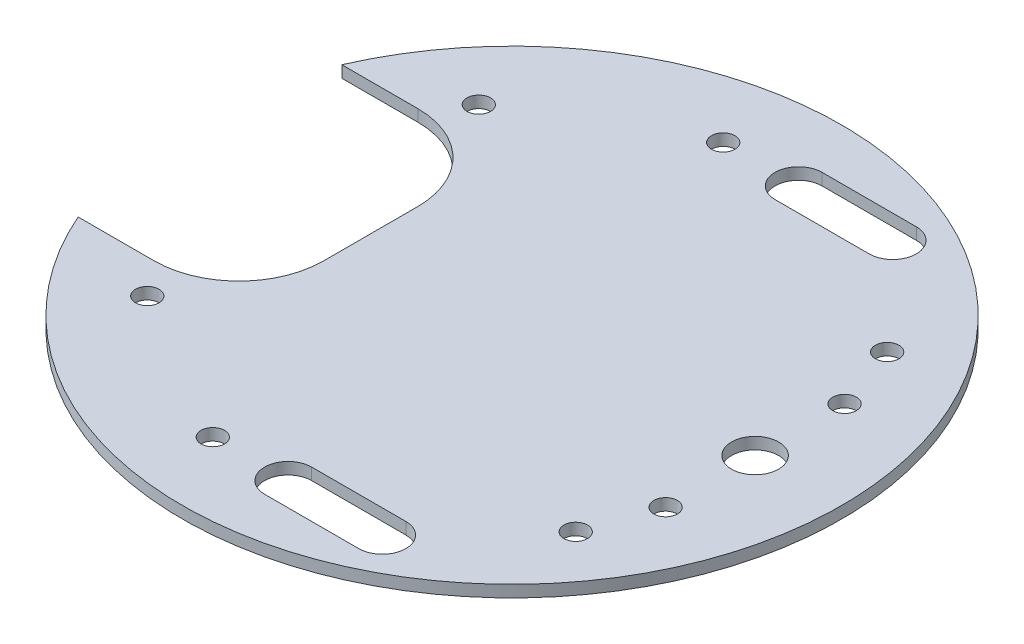
SolidWorks part; units mm, degrees
ref_plane "Front Plane" through (0, 0, 0) normal (0, 0, 1) x (1, 0, 0)
ref_plane "Top Plane" through (0, 0, 0) normal (0, 1, 0) x (1, 0, 0)
ref_plane "Right Plane" through (0, 0, 0) normal (1, 0, 0) x (0, 0, -1)
sketch "Sketch1" plane through (0, 0, 0) normal (0, 1, 0) x (1, 0, 0)
  line L0 (0, 0) -> (109.2336, 0) construction
  line L1 (0, 0) -> (-110.6657, 0) construction
  line L2 (27.076, -24.13) -> (65.5497, -24.13)
  line L3 (27.076, -24.13) -> (27.076, 24.13)
  line L4 (27.076, 24.13) -> (65.5497, 24.13)
  line L5 (65.5497, -24.13) -> (65.5497, 24.13)
  line L6 (27.076, -24.13) -> (65.5497, 24.13) construction
  line L7 (27.076, 24.13) -> (65.5497, -24.13) construction
  line L9 (-88.9, 35.56) -> (-38.1, 35.56)
  line L10 (-88.9, 35.56) -> (-88.9, -35.56)
  line L11 (-88.9, -35.56) -> (-38.1, -35.56)
  line L12 (-38.1, 35.56) -> (-38.1, -35.56)
  line L13 (-88.9, 35.56) -> (-38.1, -35.56) construction
  line L14 (-88.9, -35.56) -> (-38.1, 35.56) construction
  circle A0 centre (0, 0) radius 88.9
  circle A1 centre (0, 0) radius 69.85
  circle A2 centre (65.5497, 24.13) radius 3.175
  circle A3 centre (65.5497, -24.13) radius 3.175
  circle A4 centre (-53.6721, -44.7027) radius 3.175
  circle A5 centre (-11.8777, -68.8327) radius 3.175
  circle A6 centre (-11.8777, 68.8327) radius 3.175
  circle A7 centre (-53.6721, 44.7027) radius 3.175
  point P4 (46.3129, 0)
  point P12 (-63.5, 0)
  point P23 (0, 0)
  dimension "D1" = 177.8
  dimension "D2" = 139.7
  dimension "D4" = 3
  dimension "D3" = 48.26
  dimension "D5" = 71.12
  dimension "D6" = 50.8
  dimension "D7" = 63.5
sketch "Sketch2" plane through (0, 0, 0) normal (0, 1, 0) x (1, 0, 0)
  circle A0 centre (0, 0) radius 88.9
extrude "Boss-Extrude1" add sketch "Sketch2" along normal blind 3.175
sketch "Sketch3" plane through (0, 3.175, 0) normal (0, 1, 0) x (1, 0, 0)
  line L4 (27.076, -24.13) -> (65.5497, -24.13)
  line L5 (65.5497, -24.13) -> (65.5497, 24.13)
  line L6 (65.5497, 24.13) -> (27.076, 24.13)
  line L7 (27.076, 24.13) -> (27.076, -24.13)
  line L8 (27.076, -24.13) -> (65.5497, -24.13)
  line L9 (65.5497, -24.13) -> (65.5497, 24.13)
  line L10 (65.5497, 24.13) -> (27.076, 24.13)
  line L11 (27.076, 24.13) -> (27.076, -24.13)
  line L12 (-38.1, 35.56) -> (-88.9, 35.56)
  line L13 (-38.1, -35.56) -> (-38.1, 35.56)
  line L14 (-88.9, -35.56) -> (-38.1, -35.56)
  line L15 (-88.9, 35.56) -> (-88.9, -35.56)
  line L16 (-38.1, 35.56) -> (-88.9, 35.56)
  line L17 (-38.1, -35.56) -> (-38.1, 35.56)
  line L18 (-88.9, -35.56) -> (-38.1, -35.56)
  line L19 (-88.9, 35.56) -> (-88.9, -35.56)
  circle A1 centre (65.5497, -24.13) radius 3.175
  circle A2 centre (65.5497, -24.13) radius 3.175
  circle A3 centre (65.5497, 24.13) radius 3.175
  circle A4 centre (65.5497, 24.13) radius 3.175
  circle A5 centre (0, 0) radius 69.85
  circle A6 centre (0, 0) radius 69.85
  circle A7 centre (0, 0) radius 88.9
  circle A8 centre (0, 0) radius 88.9
  circle A9 centre (-53.6721, 44.7027) radius 3.175
  circle A10 centre (-53.6721, 44.7027) radius 3.175
  circle A11 centre (-11.8777, 68.8327) radius 3.175
  circle A12 centre (-11.8777, 68.8327) radius 3.175
  circle A13 centre (-11.8777, -68.8327) radius 3.175
  circle A14 centre (-11.8777, -68.8327) radius 3.175
  circle A15 centre (-53.6721, -44.7027) radius 3.175
  circle A16 centre (-53.6721, -44.7027) radius 3.175
  dimension "D1" = 0
  dimension "D2" = 0
  dimension "D3" = 0
  dimension "D4" = 0
  dimension "D5" = 0
  dimension "D6" = 0
  dimension "D7" = 0
  dimension "D8" = 0
  dimension "D9" = 0
  dimension "D10" = 0
extrude "Cut-Extrude1" cut sketch "Sketch3" against normal blind 3.175 contours A10 | A12 | A4 | A2 | A14 | A16 | L16 L19 L18 L17
sketch "Sketch4" plane through (0, 3.175, 0) normal (0, 1, 0) x (1, 0, 0)
  line L0 (0, 88.9) -> (0, -88.9) construction
  line L1 (88.9, 0) -> (-87.6104, 0) construction
  line L2 (52.695, -25.135) -> (52.695, -18.785)
  line L3 (-30.48, 2.54) -> (47.52, 2.54)
  line L4 (-30.48, 2.54) -> (-30.48, -57.46)
  line L5 (-30.48, -57.46) -> (47.52, -57.46)
  line L6 (47.52, 2.54) -> (47.52, -57.46)
  line L7 (-38.1, 58.62) -> (56.9, 58.62)
  line L8 (-38.1, 58.62) -> (-38.1, 7.62)
  line L9 (-38.1, 7.62) -> (56.9, 7.62)
  line L10 (56.9, 58.62) -> (56.9, 7.62)
  line L11 (56.9, 58.62) -> (53.9, 58.62)
  line L12 (56.9, 58.62) -> (56.9, 7.62)
  line L13 (56.9, 7.62) -> (53.9, 7.62)
  line L14 (53.9, 58.62) -> (53.9, 7.62)
  line L15 (56.9, 58.62) -> (61.9, 58.62)
  line L16 (56.9, 58.62) -> (56.9, 44.62)
  line L17 (56.9, 44.62) -> (61.9, 44.62)
  line L18 (61.9, 58.62) -> (61.9, 44.62)
  line L19 (47.52, 2.54) -> (44.52, 2.54)
  line L20 (47.52, 2.54) -> (47.52, -57.46)
  line L21 (47.52, -57.46) -> (44.52, -57.46)
  line L22 (44.52, 2.54) -> (44.52, -57.46)
  line L23 (47.52, 2.54) -> (47.695, 2.54)
  line L24 (47.52, 2.54) -> (47.52, -21.96)
  line L25 (47.52, -21.96) -> (47.695, -21.96)
  line L26 (47.695, 2.54) -> (47.695, -21.96)
  line L27 (52.695, -25.135) -> (42.695, -25.135)
  line L28 (52.695, -18.785) -> (42.695, -18.785)
  line L29 (42.695, -25.135) -> (42.695, -18.785)
  line L30 (52.695, -25.135) -> (42.695, -18.785) construction
  line L31 (52.695, -18.785) -> (42.695, -25.135) construction
  line L32 (69.9, 41.445) -> (69.9, 47.795)
  line L33 (69.9, 41.445) -> (53.9, 41.445)
  line L34 (69.9, 47.795) -> (53.9, 47.795)
  line L35 (53.9, 41.445) -> (53.9, 47.795)
  line L36 (69.9, 41.445) -> (53.9, 47.795) construction
  line L37 (69.9, 47.795) -> (53.9, 41.445) construction
  line L39 (-38.1, 58.62) -> (-35.1, 58.62)
  line L40 (-38.1, 58.62) -> (-38.1, 55.62)
  line L41 (-38.1, 55.62) -> (-35.1, 55.62)
  line L42 (-35.1, 58.62) -> (-35.1, 55.62)
  line L43 (-30.48, 2.54) -> (-27.48, 2.54)
  line L44 (-30.48, 2.54) -> (-30.48, -0.46)
  line L45 (-30.48, -0.46) -> (-27.48, -0.46)
  line L46 (-27.48, 2.54) -> (-27.48, -0.46)
  arc A0 (-81.4782, -35.56) -> (-81.4782, 35.56) centre (0, 0) ccw construction
  circle A1 centre (-53.6721, -44.7027) radius 7.9375
  circle A2 centre (-11.8777, -68.8327) radius 7.9375
  circle A11 centre (47.695, -21.96) radius 3.175
  circle A12 centre (61.9, 44.62) radius 3.175
  circle A13 centre (-11.8777, 68.8327) radius 7.9375
  circle A14 centre (-53.6721, 44.7027) radius 7.9375
  circle A15 centre (65.5497, -24.13) radius 7.9375
  circle A16 centre (65.5497, 24.13) radius 7.9375
  point P33 (0.7332, 3.6329)
  point P34 (0, -3.9109)
  point P61 (0, 0)
  dimension "D1" = 15.875
  dimension "D2" = 15.875
  dimension "D14" = 6.35
  dimension "D18" = 6.35
  dimension "D4" = 78
  dimension "D5" = 60
  dimension "D6" = 2.54
  dimension "D7" = 30.48
  dimension "D8" = 95
  dimension "D9" = 51
  dimension "D10" = 38.1
  dimension "D11" = 7.62
  dimension "D12" = 14
  dimension "D13" = 3
  dimension "D15" = 6.35
  dimension "D16" = 16
  dimension "D17" = 6.35
  dimension "D19" = 10
  dimension "D20" = 24.5
  dimension "D21" = 0.175
  dimension "D22" = 3
  dimension "D23" = 0
  dimension "D24" = 3
  dimension "D25" = 3
  dimension "D26" = 3
  dimension "D27" = 3
  dimension "D3" = 3
sketch "Sketch5" plane through (0, 3.175, 0) normal (0, 1, 0) x (1, 0, 0)
  line L0 (-38.1, 58.62) -> (-38.1, 7.62) construction
  line L1 (-38.1, 7.62) -> (56.9, 7.62) construction
  line L2 (56.9, 58.62) -> (56.9, 7.62) construction
  line L3 (56.9, 58.62) -> (56.9, 7.62) construction
  line L4 (56.9, 58.62) -> (53.9, 58.62) construction
  line L5 (53.9, 58.62) -> (53.9, 7.62) construction
  line L6 (56.9, 7.62) -> (53.9, 7.62) construction
  line L7 (-38.1, 58.62) -> (56.9, 58.62) construction
  line L8 (-30.48, 2.54) -> (-30.48, -57.46) construction
  line L9 (-30.48, -57.46) -> (47.52, -57.46) construction
  line L10 (47.52, 2.54) -> (47.52, -57.46) construction
  line L11 (47.52, 2.54) -> (47.52, -57.46) construction
  line L12 (47.52, 2.54) -> (44.52, 2.54) construction
  line L13 (44.52, 2.54) -> (44.52, -57.46) construction
  line L14 (47.52, -57.46) -> (44.52, -57.46) construction
  line L15 (-30.48, 2.54) -> (47.52, 2.54) construction
  line L16 (-38.1, 58.62) -> (-35.1, 58.62) construction
  line L17 (-35.1, 58.62) -> (-35.1, 55.62) construction
  line L18 (-38.1, 55.62) -> (-35.1, 55.62) construction
  line L19 (-38.1, 58.62) -> (-38.1, 55.62) construction
  line L20 (47.52, 2.54) -> (47.695, 2.54) construction
  line L21 (47.695, 2.54) -> (47.695, -21.96) construction
  line L22 (47.52, -21.96) -> (47.695, -21.96) construction
  line L23 (47.52, 2.54) -> (47.52, -21.96) construction
  line L24 (-30.48, 2.54) -> (-27.48, 2.54) construction
  line L25 (-27.48, 2.54) -> (-27.48, -0.46) construction
  line L26 (-30.48, -0.46) -> (-27.48, -0.46) construction
  line L27 (-30.48, 2.54) -> (-30.48, -0.46) construction
  line L28 (56.9, 58.62) -> (61.9, 58.62) construction
  line L29 (61.9, 58.62) -> (61.9, 44.62) construction
  line L30 (56.9, 44.62) -> (61.9, 44.62) construction
  line L31 (56.9, 58.62) -> (56.9, 44.62) construction
  line L32 (69.9, 41.445) -> (69.9, 47.795) construction
  line L33 (69.9, 47.795) -> (53.9, 47.795) construction
  line L34 (53.9, 41.445) -> (53.9, 47.795) construction
  line L35 (69.9, 41.445) -> (53.9, 41.445) construction
  line L36 (52.695, -25.135) -> (52.695, -18.785) construction
  line L37 (52.695, -18.785) -> (42.695, -18.785) construction
  line L38 (42.695, -25.135) -> (42.695, -18.785) construction
  line L39 (52.695, -25.135) -> (42.695, -25.135) construction
  line L40 (-38.1, 58.62) -> (-38.1, 7.62)
  line L41 (-38.1, 7.62) -> (56.9, 7.62)
  line L42 (56.9, 58.62) -> (56.9, 7.62)
  line L43 (56.9, 58.62) -> (56.9, 7.62)
  line L44 (56.9, 58.62) -> (53.9, 58.62)
  line L45 (53.9, 58.62) -> (53.9, 7.62)
  line L46 (56.9, 7.62) -> (53.9, 7.62)
  line L47 (-38.1, 58.62) -> (56.9, 58.62)
  line L48 (-30.48, 2.54) -> (-30.48, -57.46)
  line L49 (-30.48, -57.46) -> (47.52, -57.46)
  line L50 (47.52, 2.54) -> (47.52, -57.46)
  line L51 (47.52, 2.54) -> (47.52, -57.46)
  line L52 (47.52, 2.54) -> (44.52, 2.54)
  line L53 (44.52, 2.54) -> (44.52, -57.46)
  line L54 (47.52, -57.46) -> (44.52, -57.46)
  line L55 (-30.48, 2.54) -> (47.52, 2.54)
  line L56 (-38.1, 58.62) -> (-35.1, 58.62)
  line L57 (-35.1, 58.62) -> (-35.1, 55.62)
  line L58 (-38.1, 55.62) -> (-35.1, 55.62)
  line L59 (-38.1, 58.62) -> (-38.1, 55.62)
  line L60 (47.52, 2.54) -> (47.695, 2.54)
  line L61 (47.695, 2.54) -> (47.695, -21.96)
  line L62 (47.52, -21.96) -> (47.695, -21.96)
  line L63 (47.52, 2.54) -> (47.52, -21.96)
  line L64 (-30.48, 2.54) -> (-27.48, 2.54)
  line L65 (-27.48, 2.54) -> (-27.48, -0.46)
  line L66 (-30.48, -0.46) -> (-27.48, -0.46)
  line L67 (-30.48, 2.54) -> (-30.48, -0.46)
  line L68 (56.9, 58.62) -> (61.9, 58.62)
  line L69 (61.9, 58.62) -> (61.9, 44.62)
  line L70 (56.9, 44.62) -> (61.9, 44.62)
  line L71 (56.9, 58.62) -> (56.9, 44.62)
  line L72 (69.9, 41.445) -> (69.9, 47.795)
  line L73 (69.9, 47.795) -> (53.9, 47.795)
  line L74 (53.9, 41.445) -> (53.9, 47.795)
  line L75 (69.9, 41.445) -> (53.9, 41.445)
  line L76 (52.695, -25.135) -> (52.695, -18.785)
  line L77 (52.695, -18.785) -> (42.695, -18.785)
  line L78 (42.695, -25.135) -> (42.695, -18.785)
  line L79 (52.695, -25.135) -> (42.695, -25.135)
  circle A0 centre (-11.8777, 68.8327) radius 7.9375
  circle A1 centre (-53.6721, 44.7027) radius 7.9375
  circle A2 centre (65.5497, -24.13) radius 7.9375
  circle A3 centre (-11.8777, -68.8327) radius 7.9375 construction
  circle A4 centre (-53.6721, -44.7027) radius 7.9375 construction
  circle A5 centre (61.9, 44.62) radius 3.175 construction
  circle A6 centre (47.695, -21.96) radius 3.175 construction
  circle A7 centre (65.5497, 24.13) radius 7.9375
  circle A11 centre (-11.8777, -68.8327) radius 7.9375
  circle A12 centre (-53.6721, -44.7027) radius 7.9375
  circle A13 centre (61.9, 44.62) radius 3.175
  circle A14 centre (47.695, -21.96) radius 3.175
  point P30 (0, 0)
  dimension "D1" = 3
fillet "Fillet1" radius 22.86 2 edges at (-38.1, 1.5875, 35.56) (-38.1, 1.5875, -35.56)
sketch "Sketch6" plane through (0, 3.175, 0) normal (0, 1, 0) x (1, 0, 0)
  line L0 (-38.1, 58.62) -> (-38.1, 7.62) construction
  line L1 (-38.1, 7.62) -> (56.9, 7.62) construction
  line L2 (56.9, 58.62) -> (56.9, 7.62) construction
  line L3 (56.9, 58.62) -> (56.9, 7.62) construction
  line L4 (56.9, 58.62) -> (53.9, 58.62) construction
  line L5 (53.9, 58.62) -> (53.9, 7.62) construction
  line L6 (56.9, 7.62) -> (53.9, 7.62) construction
  line L7 (-38.1, 58.62) -> (56.9, 58.62) construction
  line L8 (-30.48, 2.54) -> (-30.48, -57.46) construction
  line L9 (-30.48, -57.46) -> (47.52, -57.46) construction
  line L10 (47.52, 2.54) -> (47.52, -57.46) construction
  line L11 (47.52, 2.54) -> (47.52, -57.46) construction
  line L12 (47.52, 2.54) -> (44.52, 2.54) construction
  line L13 (44.52, 2.54) -> (44.52, -57.46) construction
  line L14 (47.52, -57.46) -> (44.52, -57.46) construction
  line L15 (-30.48, 2.54) -> (47.52, 2.54) construction
  line L16 (-38.1, 58.62) -> (-35.1, 58.62) construction
  line L17 (-35.1, 58.62) -> (-35.1, 55.62) construction
  line L18 (-38.1, 55.62) -> (-35.1, 55.62) construction
  line L19 (-38.1, 58.62) -> (-38.1, 55.62) construction
  line L20 (47.52, 2.54) -> (47.695, 2.54) construction
  line L21 (47.695, 2.54) -> (47.695, -21.96) construction
  line L22 (47.52, -21.96) -> (47.695, -21.96) construction
  line L23 (47.52, 2.54) -> (47.52, -21.96) construction
  line L24 (-30.48, 2.54) -> (-27.48, 2.54) construction
  line L25 (-27.48, 2.54) -> (-27.48, -0.46) construction
  line L26 (-30.48, -0.46) -> (-27.48, -0.46) construction
  line L27 (-30.48, 2.54) -> (-30.48, -0.46) construction
  line L28 (56.9, 58.62) -> (61.9, 58.62) construction
  line L29 (61.9, 58.62) -> (61.9, 44.62) construction
  line L30 (56.9, 44.62) -> (61.9, 44.62) construction
  line L31 (56.9, 58.62) -> (56.9, 44.62) construction
  line L32 (69.9, 41.445) -> (69.9, 47.795) construction
  line L33 (69.9, 47.795) -> (53.9, 47.795) construction
  line L34 (53.9, 41.445) -> (53.9, 47.795) construction
  line L35 (69.9, 41.445) -> (53.9, 41.445) construction
  line L36 (52.695, -25.135) -> (52.695, -18.785) construction
  line L37 (52.695, -18.785) -> (42.695, -18.785) construction
  line L38 (42.695, -25.135) -> (42.695, -18.785) construction
  line L39 (52.695, -25.135) -> (42.695, -25.135) construction
  line L40 (-38.1, 58.62) -> (-38.1, 7.62)
  line L41 (-38.1, 7.62) -> (56.9, 7.62)
  line L42 (56.9, 58.62) -> (56.9, 7.62)
  line L43 (56.9, 58.62) -> (56.9, 7.62)
  line L44 (56.9, 58.62) -> (53.9, 58.62)
  line L45 (53.9, 58.62) -> (53.9, 7.62)
  line L46 (56.9, 7.62) -> (53.9, 7.62)
  line L47 (-38.1, 58.62) -> (56.9, 58.62)
  line L48 (-30.48, 2.54) -> (-30.48, -57.46)
  line L49 (-30.48, -57.46) -> (47.52, -57.46)
  line L50 (47.52, 2.54) -> (47.52, -57.46)
  line L51 (47.52, 2.54) -> (47.52, -57.46)
  line L52 (47.52, 2.54) -> (44.52, 2.54)
  line L53 (44.52, 2.54) -> (44.52, -57.46)
  line L54 (47.52, -57.46) -> (44.52, -57.46)
  line L55 (-30.48, 2.54) -> (47.52, 2.54)
  line L56 (-38.1, 58.62) -> (-35.1, 58.62)
  line L57 (-35.1, 58.62) -> (-35.1, 55.62)
  line L58 (-38.1, 55.62) -> (-35.1, 55.62)
  line L59 (-38.1, 58.62) -> (-38.1, 55.62)
  line L60 (47.52, 2.54) -> (47.695, 2.54)
  line L61 (47.695, 2.54) -> (47.695, -21.96)
  line L62 (47.52, -21.96) -> (47.695, -21.96)
  line L63 (47.52, 2.54) -> (47.52, -21.96)
  line L64 (-30.48, 2.54) -> (-27.48, 2.54)
  line L65 (-27.48, 2.54) -> (-27.48, -0.46)
  line L66 (-30.48, -0.46) -> (-27.48, -0.46)
  line L67 (-30.48, 2.54) -> (-30.48, -0.46)
  line L68 (56.9, 58.62) -> (61.9, 58.62)
  line L69 (61.9, 58.62) -> (61.9, 44.62)
  line L70 (56.9, 44.62) -> (61.9, 44.62)
  line L71 (56.9, 58.62) -> (56.9, 44.62)
  line L72 (69.9, 41.445) -> (69.9, 47.795)
  line L73 (69.9, 47.795) -> (53.9, 47.795)
  line L74 (53.9, 41.445) -> (53.9, 47.795)
  line L75 (69.9, 41.445) -> (53.9, 41.445)
  line L76 (52.695, -25.135) -> (52.695, -18.785)
  line L77 (52.695, -18.785) -> (42.695, -18.785)
  line L78 (42.695, -25.135) -> (42.695, -18.785)
  line L79 (52.695, -25.135) -> (42.695, -25.135)
  line L80 (8.4423, 68.8327) -> (33.8423, 68.8327) construction
  line L81 (8.4423, 75.1827) -> (33.8423, 75.1827)
  line L82 (8.4423, 62.4827) -> (33.8423, 62.4827)
  line L83 (8.4423, -68.8327) -> (33.8423, -68.8327) construction
  line L84 (8.4423, -62.4827) -> (33.8423, -62.4827)
  line L85 (8.4423, -75.1827) -> (33.8423, -75.1827)
  line L86 (0, 0) -> (103.5857, 0) construction
  line L87 (21.1423, 91.3998) -> (21.1423, -92.9891) construction
  line L88 (65.5497, 24.13) -> (65.5497, -24.13) construction
  line L89 (-11.8777, 68.8327) -> (21.1423, 68.8327)
  line L90 (-11.8777, -68.8327) -> (21.1423, -68.8327)
  circle A0 centre (-53.6721, 44.7027) radius 7.9375 construction
  circle A1 centre (-11.8777, 68.8327) radius 7.9375 construction
  circle A2 centre (-11.8777, -68.8327) radius 7.9375 construction
  circle A3 centre (-53.6721, -44.7027) radius 7.9375 construction
  circle A4 centre (65.5497, -24.13) radius 7.9375 construction
  circle A5 centre (61.9, 44.62) radius 3.175 construction
  circle A6 centre (47.695, -21.96) radius 3.175 construction
  circle A7 centre (65.5497, 24.13) radius 7.9375 construction
  circle A8 centre (-53.6721, 44.7027) radius 7.9375
  circle A9 centre (-11.8777, 68.8327) radius 7.9375
  circle A10 centre (-11.8777, -68.8327) radius 7.9375
  circle A11 centre (-53.6721, -44.7027) radius 7.9375
  circle A12 centre (65.5497, -24.13) radius 7.9375
  circle A13 centre (61.9, 44.62) radius 3.175
  circle A14 centre (47.695, -21.96) radius 3.175
  circle A15 centre (65.5497, 24.13) radius 7.9375
  arc A16 (8.4423, 75.1827) -> (8.4423, 62.4827) centre (8.4423, 68.8327) ccw
  arc A17 (33.8423, 62.4827) -> (33.8423, 75.1827) centre (33.8423, 68.8327) ccw
  arc A18 (8.4423, -62.4827) -> (8.4423, -75.1827) centre (8.4423, -68.8327) ccw
  arc A19 (33.8423, -75.1827) -> (33.8423, -62.4827) centre (33.8423, -68.8327) ccw
  circle A20 centre (65.5497, 0) radius 6.35
  point P22 (21.1423, 68.8327)
  point P31 (21.1423, -68.8327)
  dimension "D3" = 6.35
  dimension "D5" = 6.35
  dimension "D6" = 12.7
  dimension "D1" = 33.02
  dimension "D2" = 25.4
  dimension "D4" = 25.4
extrude "Cut-Extrude3" cut sketch "Sketch6" against normal through all
sketch "Sketch7" plane through (0, 3.175, 0) normal (0, 1, 0) x (1, 0, 0)
  line L0 (0, 0) -> (-38.1, 0) construction
  line L1 (-35, 62) -> (56, 62)
  line L2 (-35, 62) -> (-35, 0)
  line L3 (-35, 0) -> (56, 0)
  line L4 (56, 62) -> (56, 0)
  line L5 (-38.1, -12.7) -> (-38.1, 12.7) construction
  line L6 (59.175, 42) -> (56, 42) construction
  line L7 (56, 58.6416) -> (59.175, 58.6416)
  line L8 (56, 58.6416) -> (56, 25.3584)
  line L9 (56, 25.3584) -> (59.175, 25.3584)
  line L10 (59.175, 58.6416) -> (59.175, 25.3584)
  circle A0 centre (59.175, 42) radius 3.175
  dimension "D7" = 6.35
  dimension "D1" = 62
  dimension "D2" = 91
  dimension "D3" = 0
  dimension "D4" = 35
  dimension "D5" = 20
  dimension "D6" = 3.175
sketch "Sketch8" plane through (0, 3.175, 0) normal (0, 1, 0) x (1, 0, 0)
  line L4 (59.175, 58.6416) -> (56, 58.6416)
  line L5 (59.175, 25.3584) -> (59.175, 58.6416)
  line L6 (56, 25.3584) -> (59.175, 25.3584)
  line L7 (56, 58.6416) -> (56, 25.3584)
  line L8 (59.175, 58.6416) -> (56, 58.6416)
  line L9 (59.175, 25.3584) -> (59.175, 58.6416)
  line L10 (56, 25.3584) -> (59.175, 25.3584)
  line L11 (56, 58.6416) -> (56, 25.3584)
  line L12 (56, 62) -> (-35, 62)
  line L13 (56, 0) -> (56, 62)
  line L14 (-35, 0) -> (56, 0)
  line L15 (-35, 62) -> (-35, 0)
  line L16 (56, 62) -> (-35, 62)
  line L17 (56, 0) -> (56, 62)
  line L18 (-35, 0) -> (56, 0)
  line L19 (-35, 62) -> (-35, 0)
  circle A1 centre (59.175, 42) radius 3.175
  circle A2 centre (59.175, 42) radius 3.175
  dimension "D1" = 0
  dimension "D2" = 0
  dimension "D3" = 0
extrude "Cut-Extrude4" cut sketch "Sketch8" against normal blind 10 contours A2
mirror "Mirror1" about plane through (0, 0, 0) normal (0, 0, 1) of "Cut-Extrude4"
